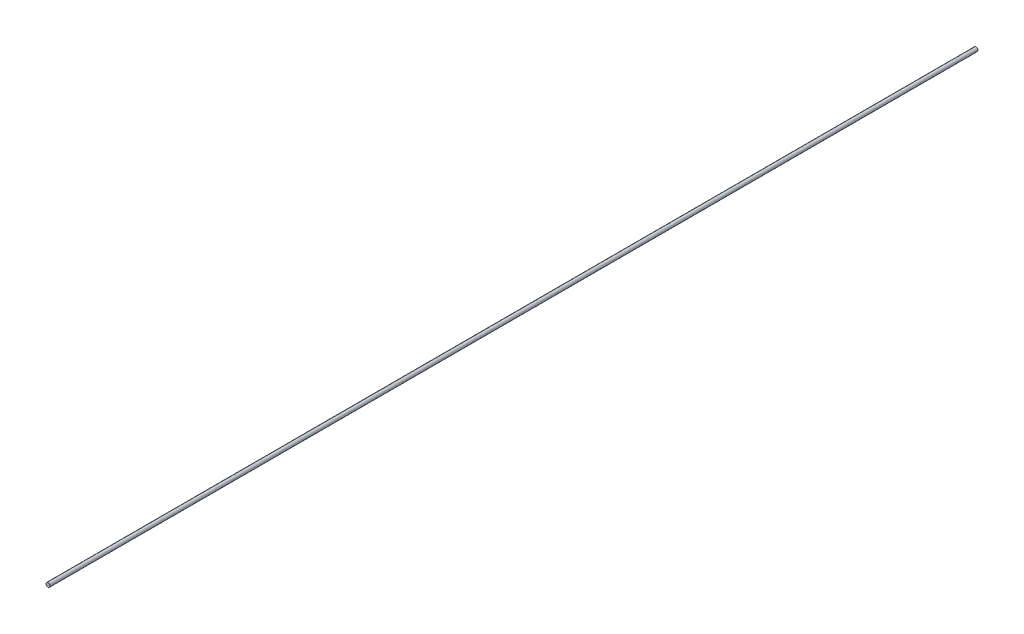
SolidWorks part; units mm, degrees
material "Poltrusion Carbon Fiber"
ref_plane "Front Plane" through (0, 0, 0) normal (0, 0, 1) x (1, 0, 0)
ref_plane "Top Plane" through (0, 0, 0) normal (0, 1, 0) x (1, 0, 0)
ref_plane "Right Plane" through (0, 0, 0) normal (1, 0, 0) x (0, 0, -1)
sketch "Эскиз1" plane through (0, 0, 0) normal (0, 0, 1) x (1, 0, 0)
  circle A0 centre (0, 0) radius 1
  dimension "D1" = 2
extrude "Бобышка-Вытянуть1" add sketch "Эскиз1" along normal blind 465
